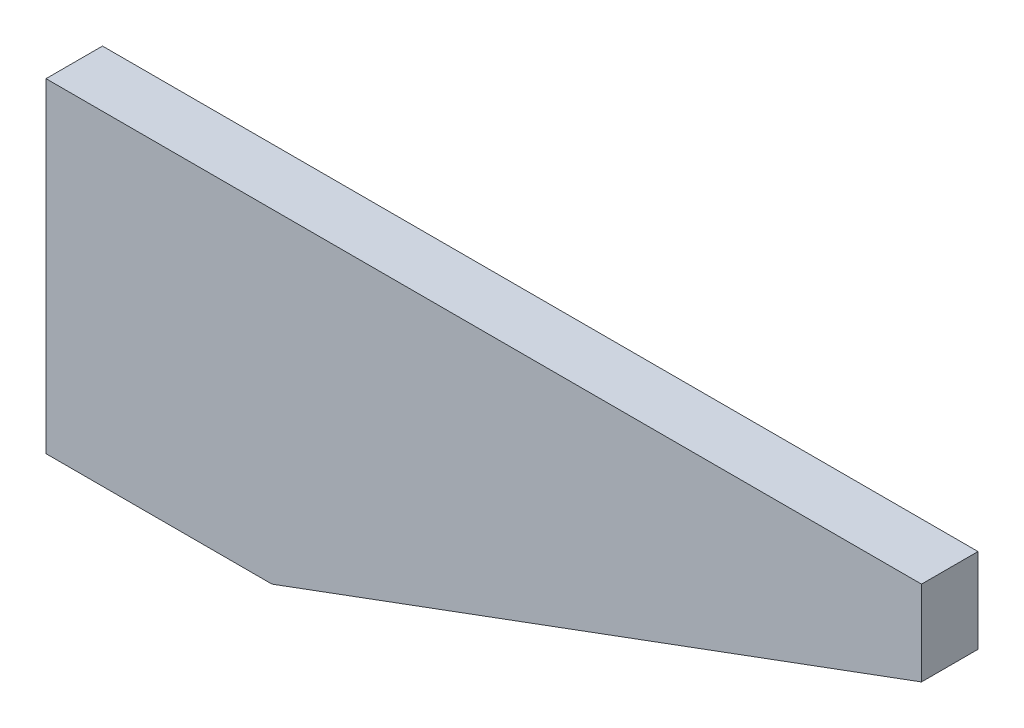
SolidWorks part; units mm, degrees
ref_plane "Plano frontal" through (0, 0, 0) normal (0, 0, 1) x (1, 0, 0)
ref_plane "Plano superior" through (0, 0, 0) normal (0, 1, 0) x (1, 0, 0)
ref_plane "Plano direito" through (0, 0, 0) normal (1, 0, 0) x (0, 0, -1)
sketch "Esboço1" plane through (0, 0, 0) normal (0, 0, 1) x (1, 0, 0)
  line L0 (-17.4568, 7.6529) -> (-17.4568, -3.8471)
  line L1 (-17.4568, 7.6529) -> (13.5432, 7.6529)
  line L2 (-17.4568, -3.8471) -> (-9.4568, -3.8471)
  line L3 (13.5432, 7.6529) -> (13.5432, 4.6529)
  line L4 (-9.4568, -3.8471) -> (13.5432, 4.6529)
  dimension "D1" = 11.5
  dimension "D2" = 31
  dimension "D3" = 8
  dimension "D4" = 3
extrude "Ressalto-extrusão1" add sketch "Esboço1" along normal blind 2
